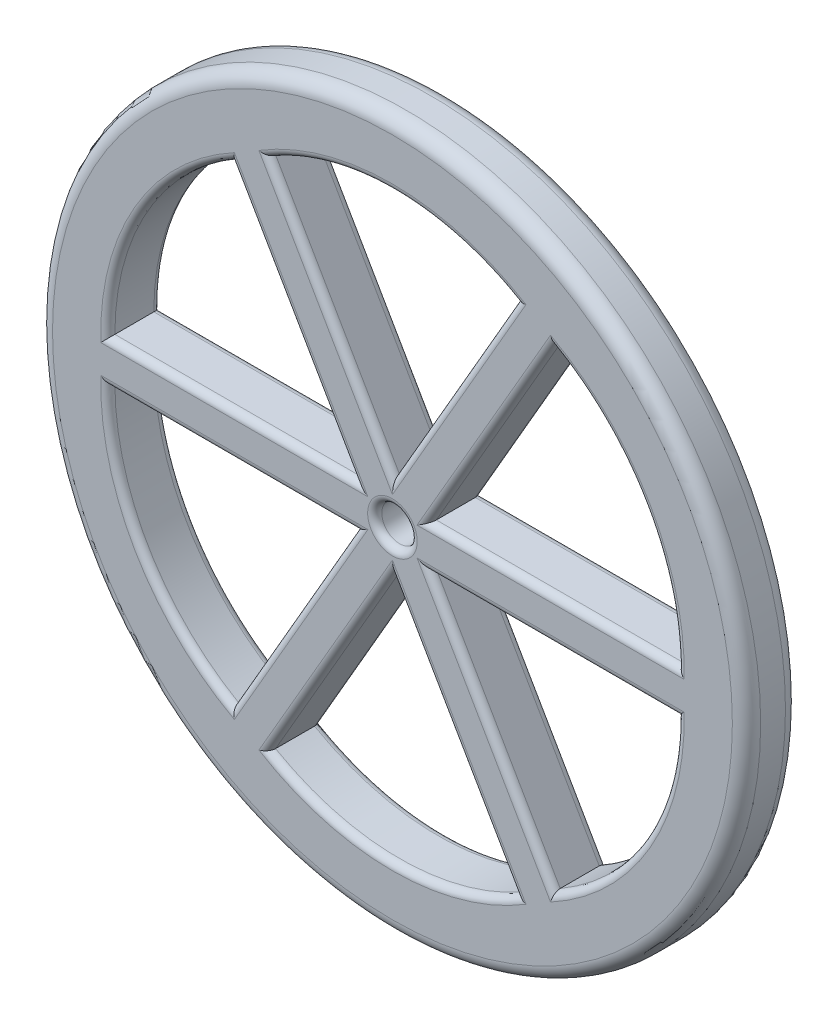
SolidWorks part; units mm, degrees
ref_plane "Front Plane" through (0, 0, 0) normal (0, 0, 1) x (1, 0, 0)
ref_plane "Top Plane" through (0, 0, 0) normal (0, 1, 0) x (1, 0, 0)
ref_plane "Right Plane" through (0, 0, 0) normal (1, 0, 0) x (0, 0, -1)
sketch "Sketch1" plane through (0, 0, 0) normal (0, 0, 1) x (1, 0, 0)
  circle A0 centre (0, 0) radius 2.5
  circle A1 centre (0, 0) radius 50
  dimension "D1" = 5
  dimension "D2" = 100
extrude "Boss-Extrude1" add sketch "Sketch1" along normal mid plane 7.5
fillet "Fillet1" radius 2 2 edges at (50, 0, -3.75) (50, 0, 3.75)
sketch "Sketch2" plane through (0, 0, 3.75) normal (0, 0, 1) x (1, 0, 0)
  line L0 (-17.5, 36.3109) -> (0, 6)
  line L1 (0, 6) -> (17.5, 36.3109)
  line L2 (0, 0) -> (0, 41) construction
  arc A0 (-17.5, 36.3109) -> (17.5, 36.3109) centre (0, 6) cw
  point P3 (0, 0)
  dimension "D3" = 35
  dimension "D1" = 60
  dimension "D2" = 6
extrude "Cut-Extrude1" cut sketch "Sketch2" against normal through all
pattern_circular "CirPattern1" count 6 over 360 about axis through (0, 0, 0) along (0, 0, 1) of "Cut-Extrude1"
fillet "Fillet3" radius 1 19 edges at (2.5, 0, -3.75) (0, 41, -3.75) (8.75, 21.1554, -3.75) (-8.75, 21.1554, -3.75) (-35.507, 20.5, -3.75) (-13.9462, 18.1554, -3.75) (-22.6962, 3, -3.75) (35.507, 20.5, -3.75) (22.6962, 3, -3.75) (13.9462, 18.1554, -3.75) (35.507, -20.5, -3.75) (13.9462, -18.1554, -3.75) (22.6962, -3, -3.75) (-35.507, -20.5, -3.75) (-22.6962, -3, -3.75) (-13.9462, -18.1554, -3.75) (0, -41, -3.75) (-8.75, -21.1554, -3.75) (8.75, -21.1554, -3.75)
fillet "Fillet4" radius 1 19 edges at (2.5, 0, 3.75) (0, 41, 3.75) (-8.75, 21.1554, 3.75) (8.75, 21.1554, 3.75) (-35.507, 20.5, 3.75) (-22.6962, 3, 3.75) (-13.9462, 18.1554, 3.75) (35.507, 20.5, 3.75) (13.9462, 18.1554, 3.75) (22.6962, 3, 3.75) (35.507, -20.5, 3.75) (22.6962, -3, 3.75) (13.9462, -18.1554, 3.75) (-35.507, -20.5, 3.75) (-13.9462, -18.1554, 3.75) (-22.6962, -3, 3.75) (0, -41, 3.75) (8.75, -21.1554, 3.75) (-8.75, -21.1554, 3.75)
